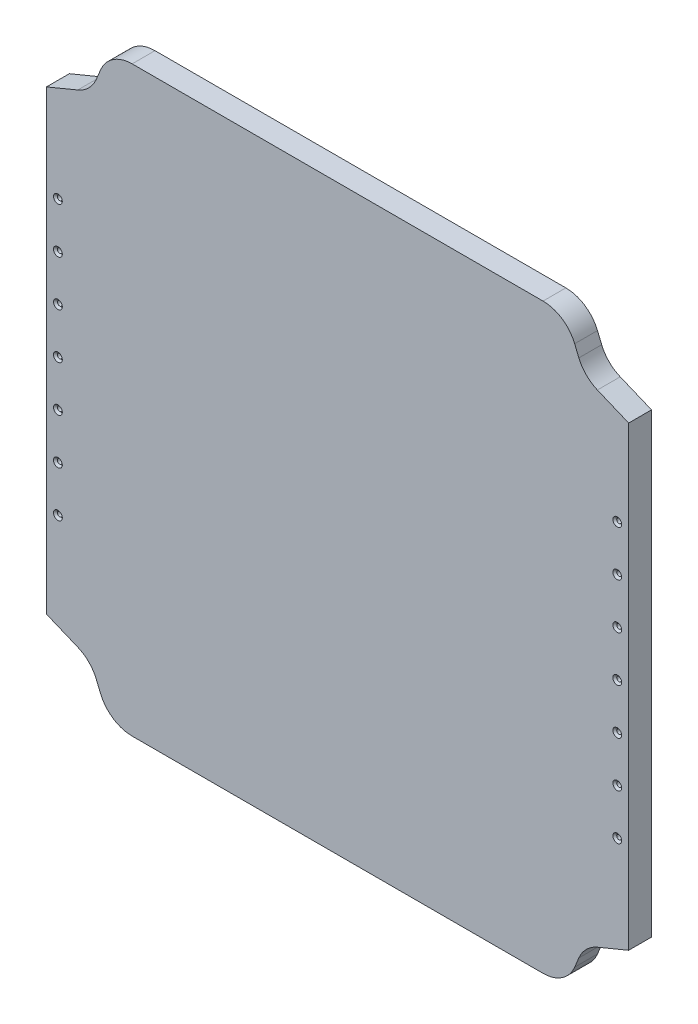
SolidWorks part; units mm, degrees
ref_plane "Front Plane" through (0, 0, 0) normal (0, 0, 1) x (1, 0, 0)
ref_plane "Top Plane" through (0, 0, 0) normal (0, 1, 0) x (1, 0, 0)
ref_plane "Right Plane" through (0, 0, 0) normal (1, 0, 0) x (0, 0, -1)
sketch "Sketch1" plane through (0, 0, 0) normal (0, 0, 1) x (1, 0, 0)
  line L0 (-254, 0) -> (254, 0)
  line L1 (254, 0) -> (274.4586, 49.3914)
  line L2 (274.4586, 49.3914) -> (323.85, 69.85)
  line L3 (323.85, 69.85) -> (323.85, 577.85)
  line L4 (0, 0) -> (0, 323.85) construction
  line L5 (0, 323.85) -> (323.85, 323.85) construction
  line L6 (-254, 647.7) -> (254, 647.7)
  line L7 (254, 647.7) -> (274.4586, 598.3086)
  line L8 (274.4586, 598.3086) -> (323.85, 577.85)
  line L9 (-254, 647.7) -> (-274.4586, 598.3086)
  line L10 (-274.4586, 598.3086) -> (-323.85, 577.85)
  line L11 (-323.85, 69.85) -> (-323.85, 577.85)
  line L12 (-274.4586, 49.3914) -> (-323.85, 69.85)
  line L13 (-254, 0) -> (-274.4586, 49.3914)
  point P16 (0, 647.7)
  dimension "D1" = 647.7
  dimension "D2" = 135
  dimension "D3" = 508
  dimension "D4" = 508
extrude "Boss-Extrude1" add sketch "Sketch1" along normal blind 25.4
fillet "Fillet1" radius 38.1 8 edges at (254, 0, 12.7) (-254, 0, 12.7) (-274.4586, 49.3914, 12.7) (-274.4586, 598.3086, 12.7) (-254, 647.7, 12.7) (254, 647.7, 12.7) (274.4586, 49.3914, 12.7) (274.4586, 598.3086, 12.7)
hole_wizard "CSK for #10 Flat Head Machine Screw (100)1" positions "Sketch2" profile "Sketch3" countersink size "#10" standard "ANSI Inch" end condition through all
sketch "Sketch2" plane through (0, 0, 25.4) normal (0, 0, 1) x (1, 0, 0)
  line L0 (323.85, 323.85) -> (311.15, 323.85) construction
  line L1 (323.85, 69.85) -> (323.85, 577.85) construction
  line L3 (311.15, 273.05) -> (311.15, 323.85)
  line L4 (311.15, 323.85) -> (311.15, 374.65)
  point P0 (311.15, 323.85)
  point P18 (311.15, 374.65)
  point P19 (311.15, 425.45)
  point P27 (311.15, 273.05)
  point P28 (311.15, 222.25)
  point P32 (311.15, 171.45)
  point P33 (311.15, 476.25)
  dimension "D1" = 12.7
  dimension "D4" = 50.8
  dimension "D5" = 50.8
  dimension "D2" = 4
  dimension "D3" = 4
sketch "Sketch3" plane through (311.15, 323.85, 25.4) normal (1, 0, 0) x (0, -1, 0)
  line L0 (0, 0) -> (0, 25.4)
  line L1 (0, 25.4) -> (2.5527, 25.4)
  line L2 (2.5527, 25.4) -> (2.5527, 1.9608)
  line L3 (2.5527, 1.9608) -> (4.8895, 0)
  line L5 (4.8895, 0) -> (0, 0)
  line L6 (-2.5527, 1.9608) -> (-4.8895, 0) construction
  line L11 (0, -6.35) -> (0, 107.95) construction
  dimension "Thru Hole Dia." = 5.1054
  dimension "Thru Hole Depth" = 25.4
  dimension "Near C'Sink Dia." = 9.779
  dimension "Near C'Sink Angle" = 100
mirror "Mirror1" about plane through (0, 0, 0) normal (1, 0, 0) of "CSK for #10 Flat Head Machine Screw (100)1"
equation "\"D5@Sketch2\"=\"D4@Sketch2\""
